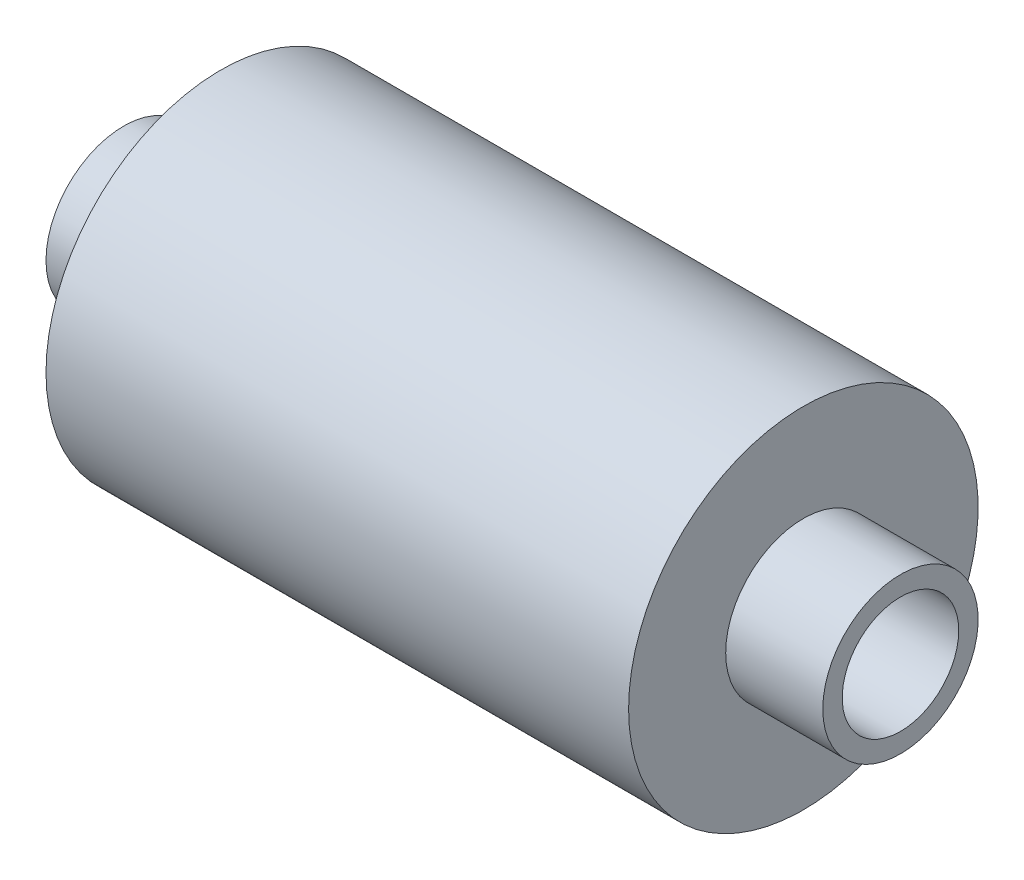
SolidWorks part; units mm, degrees
ref_plane "Front Plane" through (0, 0, 0) normal (0, 0, 1) x (1, 0, 0)
ref_plane "Top Plane" through (0, 0, 0) normal (0, 1, 0) x (1, 0, 0)
ref_plane "Right Plane" through (0, 0, 0) normal (1, 0, 0) x (0, 0, -1)
sketch "Sketch1" plane through (0, 0, 0) normal (1, 0, 0) x (0, 0, -1)
  line L0 (0, 3) -> (0, 9) construction
  circle A0 centre (0, 0) radius 3
  circle A1 centre (0, 0) radius 9
  dimension "D1" = 6
  dimension "D2" = 6
extrude "Boss-Extrude1" add sketch "Sketch1" along normal blind 40
sketch "Sketch2" plane through (0, 0, 0) normal (0, 0, 1) x (1, 0, 0)
  line L0 (0, 0) -> (40, 0) construction
  line L1 (0, 9) -> (5, 9)
  line L2 (0, 9) -> (0, 4)
  line L3 (0, 4) -> (5, 4)
  line L4 (5, 9) -> (5, 4)
  line L5 (40, 9) -> (35, 9)
  line L6 (40, 9) -> (40, 4)
  line L7 (40, 4) -> (35, 4)
  line L8 (35, 9) -> (35, 4)
  dimension "D1" = 5
  dimension "D2" = 4
revolve "Cut-Revolve1" cut sketch "Sketch2" angle 360 about L0
